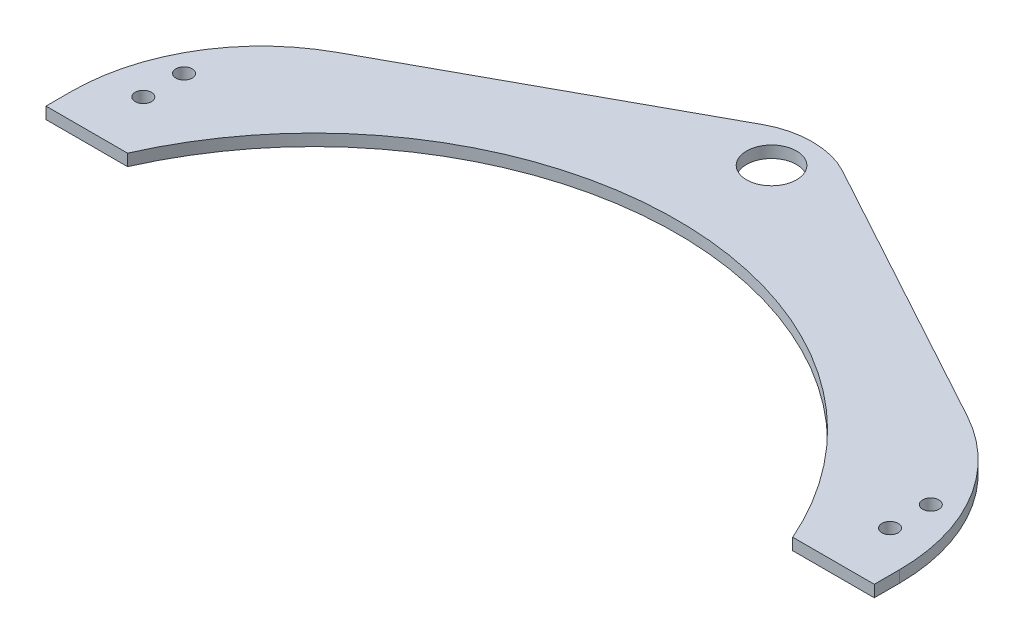
SolidWorks part; units mm, degrees
ref_plane "Front Plane" through (0, 0, 0) normal (0, 0, 1) x (1, 0, 0)
ref_plane "Top Plane" through (0, 0, 0) normal (0, 1, 0) x (1, 0, 0)
ref_plane "Right Plane" through (0, 0, 0) normal (1, 0, 0) x (0, 0, -1)
sketch "Sketch1" plane through (0, 0, 0) normal (0, 1, 0) x (1, 0, 0)
  line L0 (0, 0) -> (122.4, 0)
  line L1 (61.2, 0) -> (61.2, 39.9)
  line L2 (122.4, 0) -> (137.4, 0)
  line L3 (0, 0) -> (-15, 0)
  line L4 (137.4, 0) -> (137.4, 16.4975)
  line L5 (-15, 0) -> (-15, 16.4975)
  line L6 (61.2, 0) -> (61.2, 57.3)
  line L7 (61.2, 57.3) -> (61.2, 64.8)
  line L8 (61.2, 64.8) -> (61.3735, 64.8)
  line L9 (61.2, 64.8) -> (61.0265, 64.8)
  line L10 (68.5589, 62.967) -> (129.5853, 29.6645)
  line L11 (53.8411, 62.967) -> (-7.1853, 29.6645)
  line L12 (129.9, 0) -> (129.9, 10.4)
  line L13 (129.9, 10.4) -> (129.9, 17.9)
  line L14 (-7.5, 0) -> (-7.5, 10.4)
  line L15 (119.1658, 35.3505) -> (68.5589, 62.967)
  line L16 (137.4, 4.6274) -> (137.4, 0)
  line L17 (53.8411, 62.967) -> (3.2342, 35.3505)
  line L18 (-15, 4.6274) -> (-15, 0)
  line L19 (-7.5, 10.4) -> (-7.5, 17.9)
  arc A0 (0, 0) -> (122.4, 0) centre (61.2, -26.9726) cw
  circle A1 centre (61.2, 57.3) radius 4.6
  arc A2 (61.3735, 64.8) -> (68.5589, 62.967) centre (61.3735, 49.8) cw
  arc A3 (61.0265, 64.8) -> (53.8411, 62.967) centre (61.0265, 49.8) ccw
  arc A4 (-15, 16.4975) -> (-7.1853, 29.6645) centre (0, 16.4975) cw
  arc A5 (137.4, 16.4975) -> (129.5853, 29.6645) centre (122.4, 16.4975) ccw
  circle A6 centre (129.9, 17.9) radius 1.5
  circle A7 centre (129.9, 10.4) radius 1.5
  arc A10 (119.1658, 35.3505) -> (137.4, 4.6274) centre (102.4, 4.6274) cw
  arc A11 (3.2342, 35.3505) -> (-15, 4.6274) centre (20, 4.6274) ccw
  circle A13 centre (-7.5, 17.9) radius 1.5
  circle A14 centre (-7.5, 10.4) radius 1.5
  point P17 (65.2, 64.8)
  point P20 (57.2, 64.8)
  point P23 (-15, 25.4)
  point P26 (137.4, 25.4)
  point P41 (137.4, 25.4)
  point P44 (-15, 25.4)
  dimension "D8" = 7.5
  dimension "D11" = 15
  dimension "D12" = 15
  dimension "D15" = 10.4
  dimension "D16" = 35
  dimension "D17" = 7.5
  dimension "D1" = 122.4
  dimension "D2" = 39.9
  dimension "D3" = 15
  dimension "D4" = 15
  dimension "D5" = 25.4
  dimension "D6" = 25.4
  dimension "D7" = 57.3
  dimension "D9" = 4
  dimension "D10" = 4
  dimension "D13" = 10.4
  dimension "D14" = 7.5
extrude "Boss-Extrude2" add sketch "Sketch1" along normal blind 3.175
sketch "Sketch2" plane through (0, 3.175, 0) normal (0, 1, 0) x (1, 0, 0)
  line L1 (-67.6712, -28.5428) -> (168.2941, -28.5428)
  line L2 (-67.6712, -28.5428) -> (-67.6712, 90.1788)
  line L3 (-67.6712, 90.1788) -> (168.2941, 90.1788)
  line L4 (168.2941, -28.5428) -> (168.2941, 90.1788)
extrude "Cut-Extrude1" cut sketch "Sketch2" against normal blind 1.016
